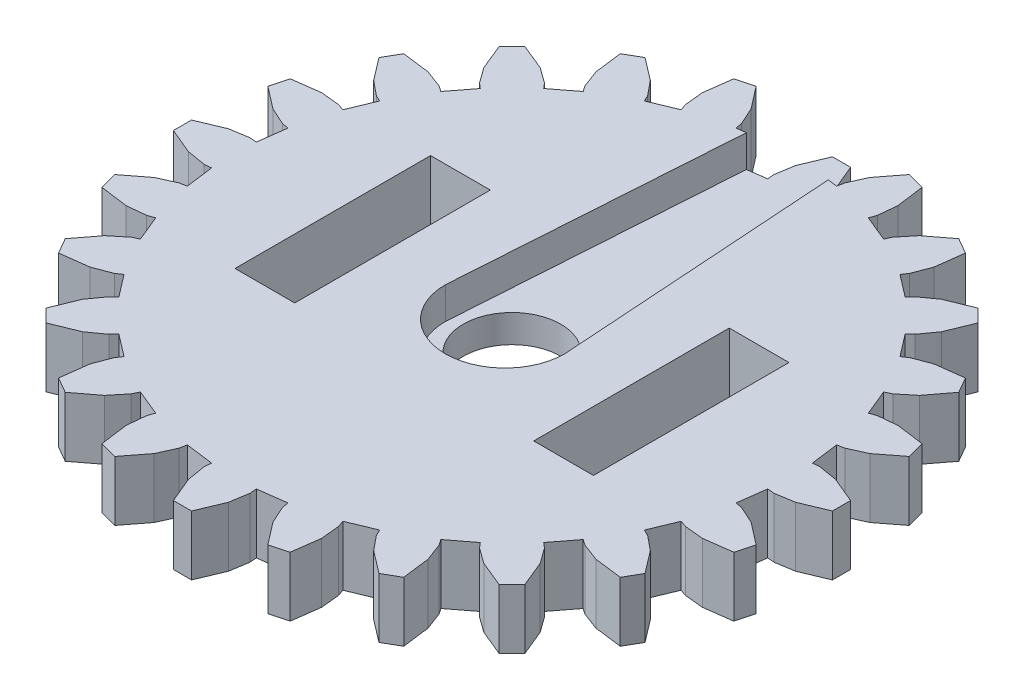
SolidWorks part; units mm, degrees
ref_plane "Front Plane" through (0, 0, 0) normal (0, 0, 1) x (1, 0, 0)
ref_plane "Top Plane" through (0, 0, 0) normal (0, 1, 0) x (1, 0, 0)
ref_plane "Right Plane" through (0, 0, 0) normal (1, 0, 0) x (0, 0, -1)
sketch "Sketch1" plane through (0, 0, 0) normal (0, 1, 0) x (1, 0, 0)
  line L0 (13.9714, 1.4647) -> (14.3221, 1.493)
  line L1 (14.3221, 1.493) -> (15.2571, 1.3398)
  line L2 (15.2571, 1.3398) -> (16.5568, 0.796)
  line L3 (16.5568, 0.796) -> (16.5568, -0.1149)
  line L4 (16.5568, -0.1149) -> (15.2571, -0.6588)
  line L5 (15.2571, -0.6588) -> (14.3221, -0.8119)
  line L6 (14.3221, -0.8119) -> (13.9714, -0.7837)
  line L7 (13.9714, -0.7837) -> (13.7867, -2.1868)
  line L8 (13.7867, -2.1868) -> (14.1327, -2.2503)
  line L9 (14.1327, -2.2503) -> (14.9963, -2.6402)
  line L10 (14.9963, -2.6402) -> (16.1109, -3.5019)
  line L11 (16.1109, -3.5019) -> (15.8751, -4.3818)
  line L12 (15.8751, -4.3818) -> (14.479, -4.5707)
  line L13 (14.479, -4.5707) -> (13.5362, -4.4766)
  line L14 (13.5362, -4.4766) -> (13.2048, -4.3586)
  line L15 (13.2048, -4.3586) -> (12.6632, -5.6661)
  line L16 (12.6632, -5.6661) -> (12.981, -5.817)
  line L17 (12.981, -5.817) -> (13.7142, -6.4171)
  line L18 (13.7142, -6.4171) -> (14.5678, -7.5379)
  line L19 (14.5678, -7.5379) -> (14.1123, -8.3268)
  line L20 (14.1123, -8.3268) -> (12.7149, -8.148)
  line L21 (12.7149, -8.148) -> (11.8285, -7.8131)
  line L22 (11.8285, -7.8131) -> (11.539, -7.6133)
  line L23 (11.539, -7.6133) -> (10.6774, -8.7361)
  line L24 (10.6774, -8.7361) -> (10.9454, -8.9641)
  line L25 (10.9454, -8.9641) -> (11.4982, -9.7335)
  line L26 (11.4982, -9.7335) -> (12.0327, -11.0371)
  line L27 (12.0327, -11.0371) -> (11.3886, -11.6812)
  line L28 (11.3886, -11.6812) -> (10.085, -11.1467)
  line L29 (10.085, -11.1467) -> (9.3156, -10.5939)
  line L30 (9.3156, -10.5939) -> (9.0876, -10.3259)
  line L31 (9.0876, -10.3259) -> (7.9648, -11.1875)
  line L32 (7.9648, -11.1875) -> (8.1646, -11.477)
  line L33 (8.1646, -11.477) -> (8.4995, -12.3634)
  line L34 (8.4995, -12.3634) -> (8.6783, -13.7608)
  line L35 (8.6783, -13.7608) -> (7.8894, -14.2163)
  line L36 (7.8894, -14.2163) -> (6.7686, -13.3627)
  line L37 (6.7686, -13.3627) -> (6.1685, -12.6295)
  line L38 (6.1685, -12.6295) -> (6.0176, -12.3117)
  line L39 (6.0176, -12.3117) -> (4.7101, -12.8533)
  line L40 (4.7101, -12.8533) -> (4.8281, -13.1847)
  line L41 (4.8281, -13.1847) -> (4.9222, -14.1275)
  line L42 (4.9222, -14.1275) -> (4.7333, -15.5236)
  line L43 (4.7333, -15.5236) -> (3.8534, -15.7594)
  line L44 (3.8534, -15.7594) -> (2.9917, -14.6448)
  line L45 (2.9917, -14.6448) -> (2.6018, -13.7812)
  line L46 (2.6018, -13.7812) -> (2.5383, -13.4352)
  line L47 (2.5383, -13.4352) -> (1.1352, -13.6199)
  line L48 (1.1352, -13.6199) -> (1.1634, -13.9706)
  line L49 (1.1634, -13.9706) -> (1.0103, -14.9056)
  line L50 (1.0103, -14.9056) -> (0.4664, -16.2053)
  line L51 (0.4664, -16.2053) -> (-0.4445, -16.2053)
  line L52 (-0.4445, -16.2053) -> (-0.9883, -14.9056)
  line L53 (-0.9883, -14.9056) -> (-1.1415, -13.9706)
  line L54 (-1.1415, -13.9706) -> (-1.1132, -13.6199)
  line L55 (-1.1132, -13.6199) -> (-2.5164, -13.4352)
  line L56 (-2.5164, -13.4352) -> (-2.5799, -13.7812)
  line L57 (-2.5799, -13.7812) -> (-2.9698, -14.6448)
  line L58 (-2.9698, -14.6448) -> (-3.8315, -15.7594)
  line L59 (-3.8315, -15.7594) -> (-4.7114, -15.5236)
  line L60 (-4.7114, -15.5236) -> (-4.9003, -14.1275)
  line L61 (-4.9003, -14.1275) -> (-4.8062, -13.1847)
  line L62 (-4.8062, -13.1847) -> (-4.6882, -12.8533)
  line L63 (-4.6882, -12.8533) -> (-5.9957, -12.3117)
  line L64 (-5.9957, -12.3117) -> (-6.1466, -12.6295)
  line L65 (-6.1466, -12.6295) -> (-6.7467, -13.3627)
  line L66 (-6.7467, -13.3627) -> (-7.8675, -14.2163)
  line L67 (-7.8675, -14.2163) -> (-8.6564, -13.7608)
  line L68 (-8.6564, -13.7608) -> (-8.4775, -12.3634)
  line L69 (-8.4775, -12.3634) -> (-8.1426, -11.477)
  line L70 (-8.1426, -11.477) -> (-7.9428, -11.1875)
  line L71 (-7.9428, -11.1875) -> (-9.0656, -10.3259)
  line L72 (-9.0656, -10.3259) -> (-9.2936, -10.5939)
  line L73 (-9.2936, -10.5939) -> (-10.0631, -11.1467)
  line L74 (-10.0631, -11.1467) -> (-11.3666, -11.6812)
  line L75 (-11.3666, -11.6812) -> (-12.0108, -11.0371)
  line L76 (-12.0108, -11.0371) -> (-11.4763, -9.7335)
  line L77 (-11.4763, -9.7335) -> (-10.9234, -8.9641)
  line L78 (-10.9234, -8.9641) -> (-10.6555, -8.7361)
  line L79 (-10.6555, -8.7361) -> (-11.517, -7.6133)
  line L80 (-11.517, -7.6133) -> (-11.8066, -7.8131)
  line L81 (-11.8066, -7.8131) -> (-12.693, -8.148)
  line L82 (-12.693, -8.148) -> (-14.0904, -8.3268)
  line L83 (-14.0904, -8.3268) -> (-14.5459, -7.5379)
  line L84 (-14.5459, -7.5379) -> (-13.6922, -6.4171)
  line L85 (-13.6922, -6.4171) -> (-12.959, -5.817)
  line L86 (-12.959, -5.817) -> (-12.6412, -5.6661)
  line L87 (-12.6412, -5.6661) -> (-13.1828, -4.3586)
  line L88 (-13.1828, -4.3586) -> (-13.5142, -4.4766)
  line L89 (-13.5142, -4.4766) -> (-14.4571, -4.5707)
  line L90 (-14.4571, -4.5707) -> (-15.8532, -4.3818)
  line L91 (-15.8532, -4.3818) -> (-16.089, -3.5019)
  line L92 (-16.089, -3.5019) -> (-14.9743, -2.6402)
  line L93 (-14.9743, -2.6402) -> (-14.1108, -2.2503)
  line L94 (-14.1108, -2.2503) -> (-13.7648, -2.1868)
  line L95 (-13.7648, -2.1868) -> (-13.9495, -0.7837)
  line L96 (-13.9495, -0.7837) -> (-14.3002, -0.8119)
  line L97 (-14.3002, -0.8119) -> (-15.2352, -0.6588)
  line L98 (-15.2352, -0.6588) -> (-16.5349, -0.1149)
  line L99 (-16.5349, -0.1149) -> (-16.5349, 0.796)
  line L100 (-16.5349, 0.796) -> (-15.2352, 1.3398)
  line L101 (-15.2352, 1.3398) -> (-14.3002, 1.493)
  line L102 (-14.3002, 1.493) -> (-13.9495, 1.4647)
  line L103 (-13.9495, 1.4647) -> (-13.7648, 2.8679)
  line L104 (-13.7648, 2.8679) -> (-14.1108, 2.9314)
  line L105 (-14.1108, 2.9314) -> (-14.9743, 3.3213)
  line L106 (-14.9743, 3.3213) -> (-16.089, 4.183)
  line L107 (-16.089, 4.183) -> (-15.8532, 5.0629)
  line L108 (-15.8532, 5.0629) -> (-14.4571, 5.2518)
  line L109 (-14.4571, 5.2518) -> (-13.5142, 5.1577)
  line L110 (-13.5142, 5.1577) -> (-13.1828, 5.0397)
  line L111 (-13.1828, 5.0397) -> (-12.6412, 6.3472)
  line L112 (-12.6412, 6.3472) -> (-12.959, 6.4981)
  line L113 (-12.959, 6.4981) -> (-13.6922, 7.0982)
  line L114 (-13.6922, 7.0982) -> (-14.5459, 8.219)
  line L115 (-14.5459, 8.219) -> (-14.0904, 9.0079)
  line L116 (-14.0904, 9.0079) -> (-12.693, 8.829)
  line L117 (-12.693, 8.829) -> (-11.8066, 8.4941)
  line L118 (-11.8066, 8.4941) -> (-11.517, 8.2943)
  line L119 (-11.517, 8.2943) -> (-10.6555, 9.4171)
  line L120 (-10.6555, 9.4171) -> (-10.9234, 9.6451)
  line L121 (-10.9234, 9.6451) -> (-11.4763, 10.4146)
  line L122 (-11.4763, 10.4146) -> (-12.0108, 11.7181)
  line L123 (-12.0108, 11.7181) -> (-11.3666, 12.3623)
  line L124 (-11.3666, 12.3623) -> (-10.0631, 11.8278)
  line L125 (-10.0631, 11.8278) -> (-9.2936, 11.2749)
  line L126 (-9.2936, 11.2749) -> (-9.0656, 11.007)
  line L127 (-9.0656, 11.007) -> (-7.9428, 11.8685)
  line L128 (-7.9428, 11.8685) -> (-8.1426, 12.1581)
  line L129 (-8.1426, 12.1581) -> (-8.4775, 13.0445)
  line L130 (-8.4775, 13.0445) -> (-8.6564, 14.4419)
  line L131 (-8.6564, 14.4419) -> (-7.8675, 14.8974)
  line L132 (-7.8675, 14.8974) -> (-6.7467, 14.0437)
  line L133 (-6.7467, 14.0437) -> (-6.1466, 13.3105)
  line L134 (-6.1466, 13.3105) -> (-5.9957, 12.9927)
  line L135 (-5.9957, 12.9927) -> (-4.6882, 13.5343)
  line L136 (-4.6882, 13.5343) -> (-4.8062, 13.8657)
  line L137 (-4.8062, 13.8657) -> (-4.9003, 14.8086)
  line L138 (-4.9003, 14.8086) -> (-4.7114, 16.2047)
  line L139 (-4.7114, 16.2047) -> (-3.8315, 16.4405)
  line L140 (-3.8315, 16.4405) -> (-2.9698, 15.3258)
  line L141 (-2.9698, 15.3258) -> (-2.5799, 14.4623)
  line L142 (-2.5799, 14.4623) -> (-2.5164, 14.1163)
  line L143 (-2.5164, 14.1163) -> (-1.1132, 14.301)
  line L144 (-1.1132, 14.301) -> (-1.1415, 14.6517)
  line L145 (-1.1415, 14.6517) -> (-0.9883, 15.5867)
  line L146 (-0.9883, 15.5867) -> (-0.4445, 16.8864)
  line L147 (-0.4445, 16.8864) -> (0.4664, 16.8864)
  line L148 (0.4664, 16.8864) -> (1.0103, 15.5867)
  line L149 (1.0103, 15.5867) -> (1.1634, 14.6517)
  line L150 (1.1634, 14.6517) -> (1.1352, 14.301)
  line L151 (1.1352, 14.301) -> (2.5383, 14.1163)
  line L152 (2.5383, 14.1163) -> (2.6018, 14.4623)
  line L153 (2.6018, 14.4623) -> (2.9917, 15.3258)
  line L154 (2.9917, 15.3258) -> (3.8534, 16.4405)
  line L155 (3.8534, 16.4405) -> (4.7333, 16.2047)
  line L156 (4.7333, 16.2047) -> (4.9222, 14.8086)
  line L157 (4.9222, 14.8086) -> (4.8281, 13.8657)
  line L158 (4.8281, 13.8657) -> (4.7101, 13.5343)
  line L159 (4.7101, 13.5343) -> (6.0176, 12.9927)
  line L160 (6.0176, 12.9927) -> (6.1685, 13.3105)
  line L161 (6.1685, 13.3105) -> (6.7686, 14.0437)
  line L162 (6.7686, 14.0437) -> (7.8894, 14.8974)
  line L163 (7.8894, 14.8974) -> (8.6783, 14.4419)
  line L164 (8.6783, 14.4419) -> (8.4995, 13.0445)
  line L165 (8.4995, 13.0445) -> (8.1646, 12.1581)
  line L166 (8.1646, 12.1581) -> (7.9648, 11.8685)
  line L167 (7.9648, 11.8685) -> (9.0876, 11.007)
  line L168 (9.0876, 11.007) -> (9.3156, 11.2749)
  line L169 (9.3156, 11.2749) -> (10.085, 11.8278)
  line L170 (10.085, 11.8278) -> (11.3886, 12.3623)
  line L171 (11.3886, 12.3623) -> (12.0327, 11.7181)
  line L172 (12.0327, 11.7181) -> (11.4982, 10.4146)
  line L173 (11.4982, 10.4146) -> (10.9454, 9.6451)
  line L174 (10.9454, 9.6451) -> (10.6774, 9.4171)
  line L175 (10.6774, 9.4171) -> (11.539, 8.2943)
  line L176 (11.539, 8.2943) -> (11.8285, 8.4941)
  line L177 (11.8285, 8.4941) -> (12.7149, 8.829)
  line L178 (12.7149, 8.829) -> (14.1123, 9.0079)
  line L179 (14.1123, 9.0079) -> (14.5678, 8.219)
  line L180 (14.5678, 8.219) -> (13.7142, 7.0982)
  line L181 (13.7142, 7.0982) -> (12.981, 6.4981)
  line L182 (12.981, 6.4981) -> (12.6632, 6.3472)
  line L183 (12.6632, 6.3472) -> (13.2048, 5.0397)
  line L184 (13.2048, 5.0397) -> (13.5362, 5.1577)
  line L185 (13.5362, 5.1577) -> (14.479, 5.2518)
  line L186 (14.479, 5.2518) -> (15.8751, 5.0629)
  line L187 (15.8751, 5.0629) -> (16.1109, 4.183)
  line L188 (16.1109, 4.183) -> (14.9963, 3.3213)
  line L189 (14.9963, 3.3213) -> (14.1327, 2.9314)
  line L190 (14.1327, 2.9314) -> (13.7867, 2.8679)
  line L191 (13.7867, 2.8679) -> (13.9714, 1.4647)
  line L192 (-13.8571, 2.1663) -> (13.879, -1.4852) construction
  circle A1 centre (0.011, 0.3405) radius 2.45
  point P198 (-13.8571, 2.1663)
  point P199 (13.879, -1.4852)
  dimension "D1" = 4.9
  dimension "D2" = 27.9755
extrude "Boss-Extrude1" add sketch "Sketch1" along normal blind 3
sketch "Sketch2" plane through (0, 3, 0) normal (0, 1, 0) x (1, 0, 0)
  line L0 (-8.989, -4.5695) -> (-5.989, -4.5695)
  line L1 (-8.989, -4.5695) -> (-8.989, 5.2505)
  line L2 (-8.989, 5.2505) -> (-5.989, 5.2505)
  line L3 (-5.989, -4.5695) -> (-5.989, 5.2505)
  line L4 (6.011, -4.5695) -> (9.011, -4.5695)
  line L5 (6.011, -4.5695) -> (6.011, 5.2505)
  line L6 (6.011, 5.2505) -> (9.011, 5.2505)
  line L7 (9.011, -4.5695) -> (9.011, 5.2505)
  circle A2 centre (0.011, 0.3405) radius 2.45 construction
  dimension "D1" = 3
  dimension "D2" = 9.82
  dimension "D3" = 3
  dimension "D4" = 9.82
  dimension "D5" = 12
  dimension "D6" = 6
  dimension "D7" = 4.91
  dimension "D8" = 4.91
extrude "Cut-Extrude1" cut sketch "Sketch2" against normal blind 3
sketch "Sketch3" plane through (0, 3, 0) normal (0, 1, 0) x (1, 0, 0)
  line L0 (0, 0) -> (0, 15) construction
  line L1 (-3, 0) -> (-1.9766, 15.3052)
  line L2 (3, 0) -> (1.9766, 15.3052)
  arc A0 (-3, 0) -> (3, 0) centre (0, 0) ccw
  arc A1 (-1.9766, 15.3052) -> (1.9766, 15.3052) centre (0, 15) cw
  point P6 (0, 17)
  dimension "D1" = 3
  dimension "D4" = 2
  dimension "D2" = 15
  dimension "D5" = 3.9531
extrude "Cut-Extrude2" cut sketch "Sketch3" against normal blind 1.6
equation "\"D7@Sketch2\"=\"D4@Sketch2\"/2"
equation "\"D8@Sketch2\"=\"D4@Sketch2\"/2"
